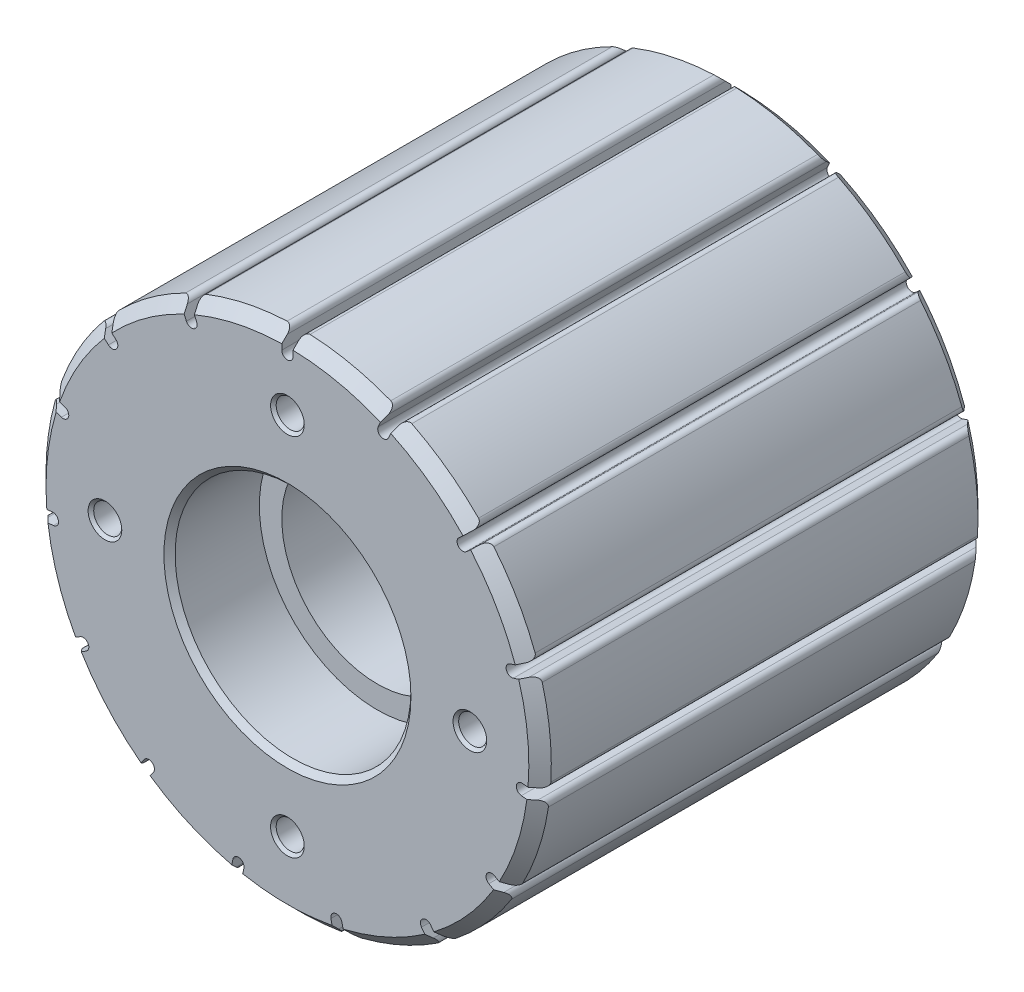
SolidWorks part; units mm, degrees
ref_plane "Front Plane" through (0, 0, 0) normal (0, 0, 1) x (1, 0, 0)
ref_plane "Top Plane" through (0, 0, 0) normal (0, 1, 0) x (1, 0, 0)
ref_plane "Right Plane" through (0, 0, 0) normal (1, 0, 0) x (0, 0, -1)
sketch "Sketch2" plane through (0, 0, 0) normal (0, 0, 1) x (1, 0, 0)
  circle A0 centre (0, 0) radius 45
  circle A1 centre (0, 0) radius 21
  dimension "D1" = 90
  dimension "D2" = 42
extrude "Boss-Extrude1" add sketch "Sketch2" along normal mid plane 80 contours A0 | A1
chamfer "Chamfer3" distance 2 angle 45 2 edges at (45, 0, 40) (45, 0, -40)
sketch "Sketch3" plane through (0, 0, 0) normal (0, 0, 1) x (1, 0, 0)
  line L0 (0, 0) -> (0, 45) construction
  line L1 (0, 45) -> (0, 42) construction
  line L2 (1, 45) -> (1, 42)
  line L3 (-1, 45) -> (-1, 42)
  circle A2 centre (0, 0) radius 45 construction
  arc A3 (1, 45) -> (-1, 45) centre (0, 45) ccw
  arc A4 (-1, 42) -> (1, 42) centre (0, 42) ccw
  point P1 (0, 43.5)
  dimension "D2" = 1
  dimension "D1" = 3
extrude "Cut-Extrude1" cut sketch "Sketch3" against normal through all both and the other way through all
fillet "Fillet1" radius 1 2 edges at (-1, 44.9889, 0) (1, 44.9889, 0)
pattern_circular "CirPattern1" count 15 over 360 about axis through (0, 0, 0) along (0, 0, 1) of "Fillet1", "Cut-Extrude1"
sketch "Sketch4" plane through (0, 0, 0) normal (0, 0, 1) x (1, 0, 0)
  circle A1 centre (0, 0) radius 17
  circle A2 centre (0, 0) radius 21 construction
  circle A3 centre (0, 0) radius 21
  dimension "D1" = 34
extrude "Boss-Extrude2" add sketch "Sketch4" along normal mid plane 48
sketch "Sketch6" plane through (0, 0, 0) normal (1, 0, 0) x (0, 0, -1)
  line L0 (0, 0) -> (56.4596, 0) construction
  line L1 (37.75, 0) -> (35.9, 0)
  line L2 (37.75, 0) -> (37.75, -23.75)
  line L3 (37.75, -23.75) -> (35.9, -23.75)
  line L4 (35.9, 0) -> (35.9, -23.75)
  line L6 (24, -17) -> (24, 17) construction
  dimension "D1" = 1.85
  dimension "D2" = 47.5
  dimension "D3" = 13.75
revolve "Cut-Revolve1" cut sketch "Sketch6" angle 360 about L0
chamfer "Chamfer2" distance 1 angle 45 2 edges at (21, 0, -40) (21, 0, 40)
sketch "Sketch8" plane through (0, 0, 40) normal (0, 0, 1) x (1, 0, 0)
  circle A0 centre (0, 0) radius 32.5 construction
  circle A1 centre (0, 32.5) radius 2.5
  dimension "D1" = 65
  dimension "D2" = 5
extrude "Cut-Extrude2" cut sketch "Sketch8" along a picked direction on the side against the normal blind 25
sketch "Sketch9" plane through (0, 0, 15) normal (0, 0, 1) x (1, 0, 0)
  circle A0 centre (0, 32.5) radius 2.5 construction
  circle A1 centre (0, 32.5) radius 2.5
extrude "Cut-Extrude3" cut sketch "Sketch9" against normal blind 3 draft 65
chamfer "Chamfer1" distance 0.5 angle 45 1 edges at (2.5, 32.5, 40)
pattern_circular "CirPattern2" count 4 over 360 about axis through (0, 0, 0) along (0, 0, 1) of "Cut-Extrude2", "Cut-Extrude3", "Chamfer1"
equation "\"d_ext_rouleau\"= 90"
equation "\"D1@Sketch2\"=\"d_ext_rouleau\""
equation "\"epaisseur_rouleau\"=80"
equation "\"D1@Boss-Extrude1\"=\"epaisseur_rouleau\""
equation "\"alesage-rouleau\"= 52"
equation "\"D2@Sketch2\"=\"d_ext_roulement_rouleau\""
equation "\"jeu_dent_rouleau\"= 2"
equation "\"profondeur_dent_rouleau\"=4"
equation "\"D2@Sketch3\"=\"jeu_dent_rouleau\"/2"
equation "\"D1@Sketch3\"=\"profondeur_dent_rouleau\"-\"D2@Sketch3\""
equation "\"D1@Fillet1\"=\"jeu_dent_rouleau\"/2"
equation "\"n_dent_roueau\"= 15"
equation "\"D1@CirPattern1\"=\"n_dent_roueau\""
equation "\"D1@Sketch4\"=\"d_ext_roulement_rouleau\"-8"
equation "\"B_roulement_rouleau\"= 12"
equation "\"D1@Boss-Extrude2\"=\"epaisseur_rouleau\" - ((\"B_roulement_rouleau\" + 4)*2)"
equation "\"F_anneau_alesage_rouleau\"=1.85"
equation "\"D1@Sketch6\"=\"F_anneau_alesage_rouleau\""
equation "\"G_anneau_alesage_rouleau\"=47.5"
equation "\"D2@Sketch6\"=\"G_anneau_alesage_rouleau\""
equation "\"K_anneau_alesage_rouleau\"=3.75"
equation "\"d_vis_flasque_rouleau\"=5"
equation "\"D2@Sketch8\"=\"d_vis_flasque_rouleau\""
equation "\"h_matrice\"= 22"
equation "\"d_matrice\"= 220"
equation "\"d_granulat\"= 8"
equation "\"zone_vide_matrice\" = 48"
equation "\"d_alesage_matrice\"=20"
equation "\"a_clavette_alesage_matrice\"=6"
equation "\"entrax_vis_rouleau\"=65"
equation "\"D1@Sketch8\"=\"entrax_vis_rouleau\""
equation "\"l-x_vis_flasque_rouleau\"=4"
equation "\"d_ext_roulement_rouleau\"= 42"
equation "\"d_int_roulement_rouleau\"= 20"
equation "\"D3@Sketch6\"=\"B_roulement_rouleau\"+1.75"
